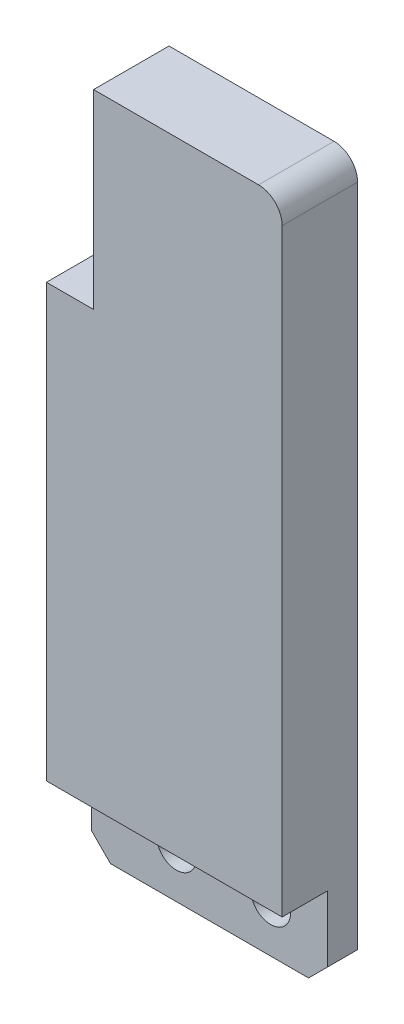
SolidWorks part; units mm, degrees
material "1060 Alloy"
ref_plane "Front Plane" through (0, 0, 0) normal (0, 0, 1) x (1, 0, 0)
ref_plane "Top Plane" through (0, 0, 0) normal (0, 1, 0) x (1, 0, 0)
ref_plane "Right Plane" through (0, 0, 0) normal (1, 0, 0) x (0, 0, -1)
sketch "Sketch1" plane through (0, 0, 0) normal (0, 0, 1) x (1, 0, 0)
  line L1 (12.5, -37.5) -> (-12.5, -37.5)
  line L2 (12.5, -37.5) -> (12.5, 37.5)
  line L3 (12.5, 37.5) -> (-12.5, 37.5)
  line L4 (-12.5, -37.5) -> (-12.5, 37.5)
  line L5 (12.5, -37.5) -> (-12.5, 37.5) construction
  line L6 (12.5, 37.5) -> (-12.5, -37.5) construction
  point P0 (0, 0)
  dimension "D1" = 75
  dimension "D2" = 25
extrude "Boss-Extrude1" add sketch "Sketch1" along normal mid plane 8
sketch "Sketch2" plane through (0, 0, 4) normal (0, 0, 1) x (1, 0, 0)
  line L0 (-12.5, 37.5) -> (-12.5, -37.5) construction
  line L1 (-12.5, 17.3) -> (-7.5, 17.3)
  line L2 (-12.5, 17.3) -> (-12.5, 37.5)
  line L3 (-12.5, 37.5) -> (-7.5, 37.5)
  line L4 (-7.5, 17.3) -> (-7.5, 37.5)
  line L5 (-12.5, 17.3) -> (-7.5, 37.5) construction
  line L6 (-12.5, 37.5) -> (-7.5, 17.3) construction
  line L7 (12.5, 37.5) -> (-12.5, 37.5) construction
  point P4 (-10, 27.4)
  dimension "D1" = 20.2
  dimension "D2" = 5
extrude "Cut-Extrude1" cut sketch "Sketch2" against normal through all contours L4 L3 L2 L1
sketch "Sketch3" plane through (0, 0, 4) normal (0, 0, 1) x (1, 0, 0)
  line L0 (12.5, -37.5) -> (12.5, 37.5) construction
  line L1 (-12.5, -37.5) -> (12.5, -37.5)
  line L2 (-12.5, -37.5) -> (-12.5, -28.5)
  line L3 (-12.5, -28.5) -> (12.5, -28.5)
  line L4 (12.5, -37.5) -> (12.5, -28.5)
  line L5 (-12.5, -37.5) -> (12.5, -28.5) construction
  line L6 (-12.5, -28.5) -> (12.5, -37.5) construction
  point P4 (0, -33)
  dimension "D1" = 9
extrude "Cut-Extrude2" cut sketch "Sketch3" against normal offset from surface (4.8 mm away) 3.2 up to face at (-2.5, 5.7667, -4)
fillet "Fillet1" radius 2.5 1 edges at (12.5, 37.5, 0)
chamfer "Chamfer1" distance 2 angle 45 2 edges at (-12.5, -37.5, -2.4) (12.5, -37.5, -2.4)
hole_wizard "Tapped Hole for M4x0.7 Helicoil1" positions "Sketch4" profile "Sketch5" tap size "M4x0.7" standard "Helicoil® Metric"
sketch "Sketch4" plane through (-7.5, 0, 0) normal (-1, 0, 0) x (0, 0, 1)
  line L0 (0, 32.5) -> (0, 22.5) construction
  line L4 (-4, 37.5) -> (4, 37.5) construction
  point P0 (0, 22.5)
  point P2 (0, 32.5)
  dimension "D1" = 10
  dimension "D2" = 5
sketch "Sketch5" plane through (-7.5, 22.5, 0) normal (0, 1, 0) x (0, 0, 1)
  line L0 (0, 0) -> (0, 8.0618)
  line L1 (0, 8.0618) -> (2.1, 6.8)
  line L2 (2.1, 6.8) -> (2.1, 0)
  line L5 (2.1, 0) -> (0, 0)
  line L10 (0, 8.0618) -> (-2.1, 6.8) construction
  line L11 (0, -6.35) -> (0, 107.95) construction
  dimension "Tap Drill Dia." = 4.2
  dimension "Tap Drill Depth" = 6.8
  dimension "Drill Angle" = 118
cosmetic thread "Hole Thread1" parameters "D1"=4.7, "D2"=5.007
cosmetic thread "Hole Thread2" parameters "D1"=4.7, "D2"=5.007
hole_wizard "M4 Clearance Hole1" positions "Sketch6" profile "Sketch7" hole size "M4" standard "ISO" end condition through all
sketch "Sketch6" plane through (0, 0, -4) normal (0, 0, -1) x (-1, 0, 0)
  point P2 (-6.483, -32.5028)
  point P5 (3.517, -32.5028)
sketch "Sketch7" plane through (6.483, -32.5028, -4) normal (1, 0, 0) x (0, 1, 0)
  line L0 (0, 0) -> (0, 8)
  line L1 (0, 8) -> (2.1, 8)
  line L2 (2.1, 8) -> (2.1, 0)
  line L5 (2.1, 0) -> (0, 0)
  line L11 (0, -6.35) -> (0, 107.95) construction
  dimension "Thru Hole Dia." = 4.2
  dimension "Thru Hole Depth" = 8
